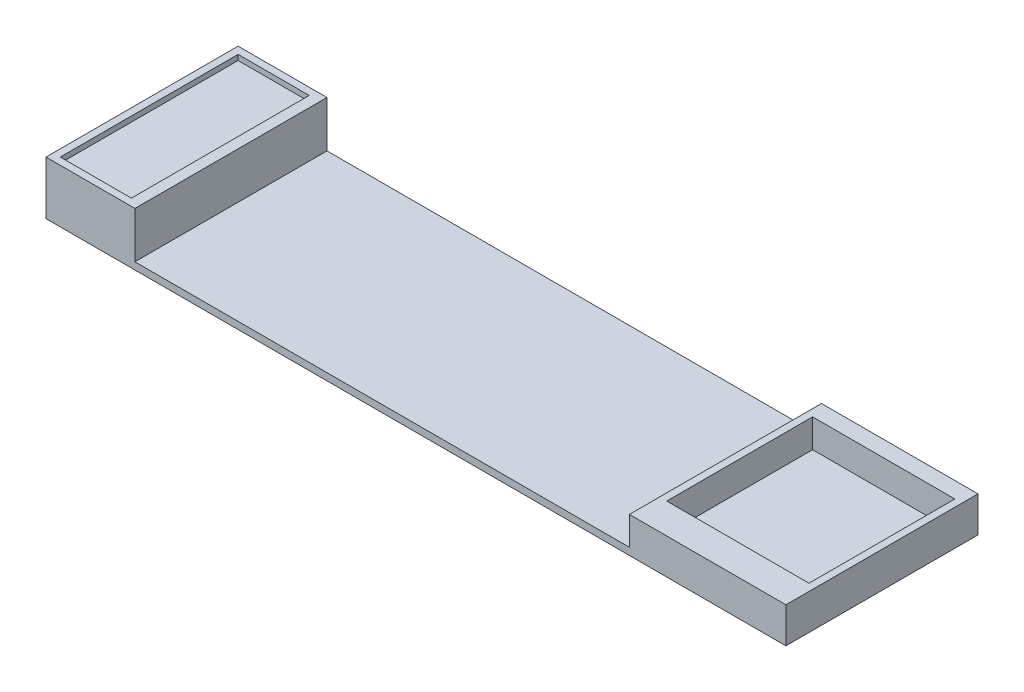
SolidWorks part; units mm, degrees
ref_plane "Front Plane" through (0, 0, 0) normal (0, 0, 1) x (1, 0, 0)
ref_plane "Top Plane" through (0, 0, 0) normal (0, 1, 0) x (1, 0, 0)
ref_plane "Right Plane" through (0, 0, 0) normal (1, 0, 0) x (0, 0, -1)
sketch "Sketch2" plane through (0, 0, 0) normal (0, 1, 0) x (1, 0, 0)
  line L1 (104, -27) -> (-104, -27)
  line L2 (104, -27) -> (104, 27)
  line L3 (104, 27) -> (-104, 27)
  line L4 (-104, -27) -> (-104, 27)
  line L5 (104, -27) -> (-104, 27) construction
  line L6 (104, 27) -> (-104, -27) construction
  point P0 (0, 0)
  dimension "D1" = 208
  dimension "D2" = 54
extrude "Boss-Extrude1" add sketch "Sketch2" along normal blind 10
sketch "Sketch3" plane through (0, 10, 0) normal (0, 1, 0) x (1, 0, 0)
  line L0 (-104, -27) -> (104, -27) construction
  line L1 (104, -27) -> (104, 27) construction
  line L2 (104, 27) -> (-104, 27) construction
  line L3 (102, -18.5) -> (62, -18.5)
  line L4 (102, -18.5) -> (102, 22.5)
  line L5 (102, 22.5) -> (62, 22.5)
  line L6 (62, -18.5) -> (62, 22.5)
  line L7 (102, -18.5) -> (62, 22.5) construction
  line L8 (102, 22.5) -> (62, -18.5) construction
  line L9 (60, -27) -> (60, 27) construction
  point P0 (60, -27)
  point P1 (60, -27)
  point P6 (82, 2)
  point P11 (82, 22.5)
  point P14 (82, -18.5)
  point P17 (60, 0)
  dimension "D1" = 44
  dimension "D2" = 4.5
  dimension "D3" = 41
  dimension "D4" = 8.5
  dimension "D5" = 40
  dimension "D6" = 2
sketch "Sketch4" plane through (0, 10, 0) normal (0, 1, 0) x (1, 0, 0)
  line L0 (-104, 27) -> (-104, -27) construction
  line L1 (-82, -25) -> (-102, -25)
  line L2 (-82, -25) -> (-82, 25)
  line L3 (-82, 25) -> (-102, 25)
  line L4 (-102, -25) -> (-102, 25)
  line L5 (-82, -25) -> (-102, 25) construction
  line L6 (-82, 25) -> (-102, -25) construction
  line L7 (-104, -27) -> (104, -27) construction
  line L8 (104, 27) -> (-104, 27) construction
  line L9 (-79, 27) -> (-79, -27) construction
  line L10 (-79, -27) -> (60, -27) construction
  line L11 (60, -27) -> (60, 27) construction
  line L12 (60, 27) -> (-79, 27) construction
  line L13 (-79, 27) -> (-79, -27) construction
  line L14 (-79, 27) -> (-79, -27)
  line L15 (-79, -27) -> (60, -27)
  line L16 (60, -27) -> (60, 27)
  line L17 (60, 27) -> (-79, 27)
  line L18 (-104, 27) -> (-79, 27)
  line L19 (-79, -27) -> (-104, -27)
  line L20 (-104, -27) -> (-104, 27)
  point P0 (-92, 0)
  point P5 (-102, 0)
  point P10 (-92, -25)
  point P11 (-79, 27)
  dimension "D1" = 2
  dimension "D2" = 2
  dimension "D3" = 50
  dimension "D4" = 20
  dimension "D5" = 25
extrude "Cut-Extrude1" cut sketch "Sketch4" against normal blind 8 contours L17 L14 L15 L16
extrude "Cut-Extrude2" cut sketch "Sketch3" against normal blind 8
sketch "Sketch6" plane through (0, 10, 0) normal (0, 1, 0) x (1, 0, 0)
  line L0 (-104, 27) -> (-79, 27)
  line L1 (-79, 27) -> (-79, -27)
  line L2 (-79, -27) -> (-104, -27)
  line L3 (-104, -27) -> (-104, 27)
extrude "Boss-Extrude2" add sketch "Sketch6" along normal blind 5
sketch "Sketch7" plane through (0, 15, 0) normal (0, 1, 0) x (1, 0, 0)
  line L0 (-104, 27) -> (-104, -27) construction
  line L1 (-102, -25) -> (-82, -25)
  line L2 (-102, -25) -> (-102, 25)
  line L3 (-102, 25) -> (-82, 25)
  line L4 (-82, -25) -> (-82, 25)
  line L5 (-102, -25) -> (-82, 25) construction
  line L6 (-102, 25) -> (-82, -25) construction
  line L7 (-79, 27) -> (-104, 27) construction
  point P0 (-92, 0)
  point P5 (-102, 0)
  point P8 (-92, 25)
  dimension "D1" = 2
  dimension "D2" = 50
  dimension "D3" = 20
  dimension "D4" = 2
extrude "Cut-Extrude3" cut sketch "Sketch7" against normal blind 1.5
